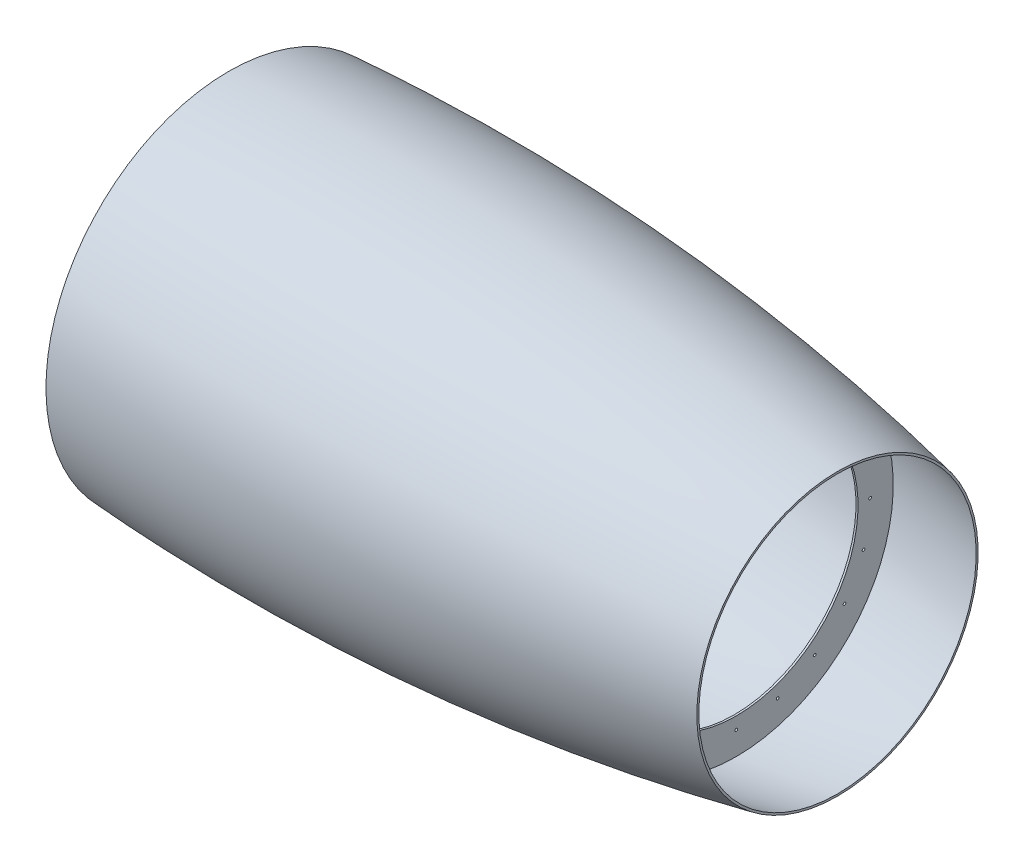
SolidWorks part; units mm, degrees
ref_plane "Front Plane" through (0, 0, 0) normal (0, 0, 1) x (1, 0, 0)
ref_plane "Top Plane" through (0, 0, 0) normal (0, 1, 0) x (1, 0, 0)
ref_plane "Right Plane" through (0, 0, 0) normal (1, 0, 0) x (0, 0, -1)
sketch "Sketch1" plane through (0, 0, 0) normal (0, 0, 1) x (1, 0, 0)
  line L0 (433.3879, 0) -> (-433.3879, 0) construction
  line L1 (-452, 244) -> (-452, 271.6243)
  line L2 (-455, 244) -> (-455, 273.1463)
  line L3 (-455, 244) -> (-452, 244)
  line L4 (-303.8508, 277.3157) -> (-303.8508, 225)
  line L5 (-303.8508, 225) -> (-300.8508, 225)
  line L6 (-300.8508, 225) -> (-300.8508, 277.366)
  line L7 (303.6642, 182) -> (303.6642, 234.6817)
  line L8 (300.6642, 182) -> (303.6642, 182)
  line L9 (300.6642, 182) -> (300.6642, 235.1562)
  line L10 (455, 210.25) -> (455, 207.25)
  arc A0 (-455, 273.1463) -> (455, 210.25) centre (-233.6716, -3139.1209) cw
  arc A1 (-452, 271.6243) -> (-303.8508, 277.3157) centre (-243.804, -3216.7652) cw
  arc A2 (-300.8508, 277.366) -> (300.6642, 235.1562) centre (-243.804, -3216.7652) cw
  arc A3 (303.6642, 234.6817) -> (455, 207.25) centre (-243.804, -3216.7652) cw
  point P4 (0, 0)
  dimension "D2" = 3
  dimension "D1" = 274
  dimension "D3" = 182
  dimension "D4" = 225
  dimension "D5" = 910
  dimension "D6" = 3
revolve "Revolve1" add sketch "Sketch1" angle 360 about L0
sketch "Sketch3" plane through (-455, 0, 0) normal (-1, 0, 0) x (0, 0, 1)
  line L0 (40, 256.9047) -> (0, 0) construction
  circle A0 centre (40, 256.9047) radius 4
  dimension "D3" = 8
  dimension "D1" = 40
  dimension "D2" = 260
extrude "Cut-Extrude1" cut sketch "Sketch3" against normal blind 10
sketch "Sketch4" plane through (303.6642, 0, 0) normal (1, 0, 0) x (0, 0, -1)
  circle A0 centre (0, 200) radius 2
  dimension "D1" = 4
  dimension "D2" = 200
extrude "Cut-Extrude2" cut sketch "Sketch4" against normal blind 10
pattern_circular "CirPattern1" count 20 over 360 about axis through (0, 0, 0) along (1, 0, 0) of "Cut-Extrude1", "Cut-Extrude2"
